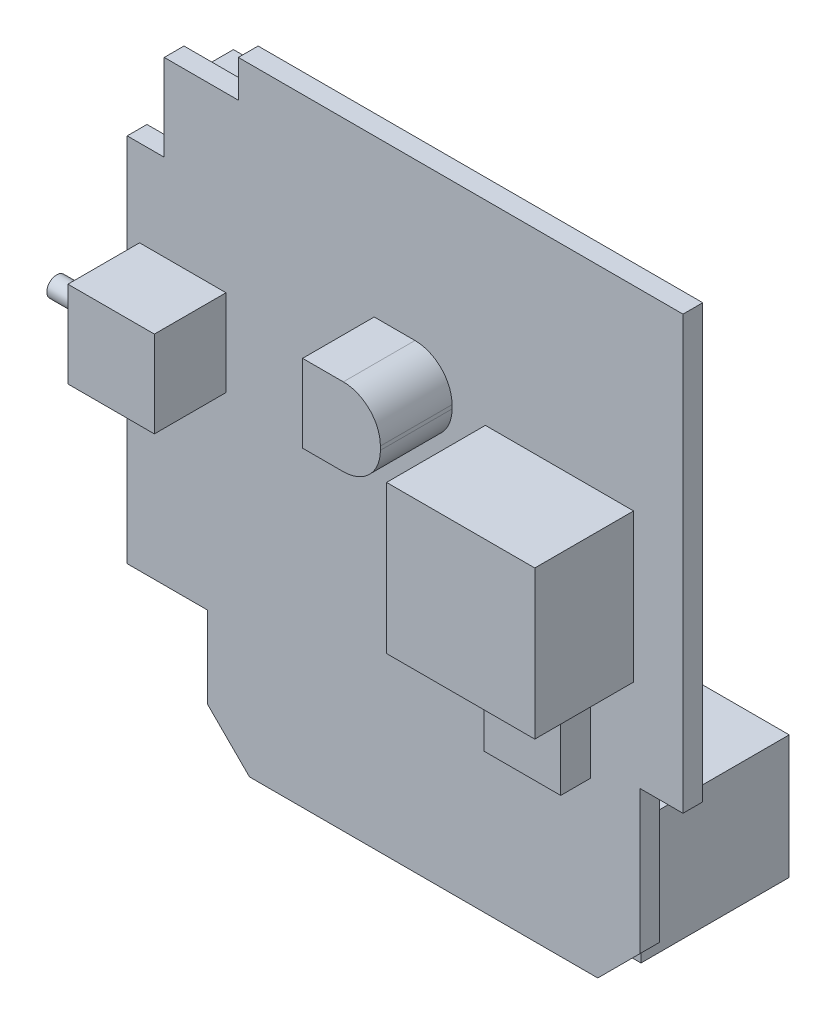
SolidWorks part; units mm, degrees
ref_plane "Front" through (0, 0, 0) normal (0, 0, 1) x (1, 0, 0)
ref_plane "Top" through (0, 0, 0) normal (0, 1, 0) x (1, 0, 0)
ref_plane "Right" through (0, 0, 0) normal (1, 0, 0) x (0, 0, -1)
sketch "Sketch1" plane through (0, 0, 0) normal (0, 0, 1) x (1, 0, 0)
  line L0 (41.5, 3.4) -> (38.1, 0)
  line L1 (9.9, 0) -> (38.1, 0)
  line L2 (6.5, 3.4) -> (6.5, 10)
  line L3 (9, 50) -> (45, 50)
  line L4 (45, 15) -> (45, 50)
  line L5 (45, 15) -> (41.5, 15)
  line L6 (6.5, 3.4) -> (9.9, 0)
  line L7 (41.5, 15) -> (41.5, 3.4)
  line L8 (0, 40) -> (0, 10)
  line L9 (6.5, 10) -> (0, 10)
  line L10 (3, 47) -> (3, 40)
  line L11 (3, 40) -> (0, 40)
  line L12 (9, 50) -> (9, 47)
  line L13 (9, 47) -> (3, 47)
  dimension "D2" = 50
  dimension "D3" = 41.5
  dimension "D4" = 135
  dimension "D5" = 45
  dimension "D6" = 10
  dimension "D7" = 3
  dimension "D8" = 40
  dimension "D9" = 135
  dimension "D10" = 6.5
  dimension "D11" = 47
  dimension "D12" = 9
  dimension "D13" = 3.4
  dimension "D14" = 3.4
  dimension "D15" = 15
extrude "Extrude1" add sketch "Sketch1" along normal blind 1.6
sketch "Sketch3" plane through (0, 0, 0) normal (0, 0, -1) x (-1, 0, 0)
  line L1 (-4.5, 46.25) -> (-10.5, 46.25)
  line L2 (-4.5, 46.25) -> (-4.5, 44.25)
  line L3 (-4.5, 44.25) -> (-10.5, 44.25)
  line L4 (-10.5, 46.25) -> (-10.5, 44.25)
  line L5 (-4.5, 16.75) -> (-10.5, 16.75)
  line L6 (-4.5, 16.75) -> (-4.5, 14.75)
  line L7 (-4.5, 14.75) -> (-10.5, 14.75)
  line L8 (-10.5, 16.75) -> (-10.5, 14.75)
  line L10 (0, 40) -> (0, 10) construction
  line L11 (6, 30.5) -> (-26.2061, 30.5) construction
  line L12 (-45, 50) -> (-9, 50) construction
  dimension "D1" = 2
  dimension "D2" = 6
  dimension "D3" = 13.75
  dimension "D4" = 4.5
  dimension "D5" = 27.5
  dimension "D6" = 19.5
extrude "Extrude3" add sketch "Sketch3" along normal blind 2.5
sketch "Sketch4" plane through (0, 0, 0) normal (0, 0, -1) x (-1, 0, 0)
  line L2 (-45, 15) -> (-45, 50) construction
  line L3 (-40, 1.2) -> (-30, 1.2)
  line L4 (-40, 1.2) -> (-40, 11.2)
  line L5 (-40, 11.2) -> (-30, 11.2)
  line L6 (-30, 1.2) -> (-30, 11.2)
  line L8 (-9.9, 0) -> (-38.1, 0) construction
  line L9 (-29, 1.2) -> (-19, 1.2)
  line L10 (-29, 1.2) -> (-29, 11.2)
  line L11 (-29, 11.2) -> (-19, 11.2)
  line L12 (-19, 1.2) -> (-19, 11.2)
  line L13 (-18, 1.2) -> (-8, 1.2)
  line L14 (-18, 1.2) -> (-18, 11.2)
  line L15 (-18, 11.2) -> (-8, 11.2)
  line L16 (-8, 1.2) -> (-8, 11.2)
  dimension "D1" = 10
  dimension "D2" = 10
  dimension "D3" = 5
  dimension "D4" = 1.2
  dimension "D5" = 1
extrude "Extrude4" add sketch "Sketch4" along normal blind 12
sketch "Sketch6" plane through (0, 0, 1.6) normal (0, 0, 1) x (1, 0, 0)
  line L0 (0, 40) -> (0, 10) construction
  line L1 (1, 33) -> (8, 33)
  line L2 (1, 33) -> (1, 26)
  line L3 (1, 26) -> (8, 26)
  line L4 (8, 33) -> (8, 26)
  line L6 (45, 50) -> (9, 50) construction
  dimension "D1" = 7
  dimension "D2" = 1
  dimension "D3" = 17
  dimension "D4" = 7
extrude "Extrude5" add sketch "Sketch6" along normal blind 5.8
sketch "Sketch8" plane through (1, 0, 4) normal (1, 0, 0) x (0, 0, -1)
  line L0 (-0.5, 33) -> (-0.5, 26) construction
  line L3 (-3.4, 33) -> (2.4, 33) construction
  line L4 (-3.4, 26) -> (2.4, 26) construction
  circle A0 centre (-0.5, 29.5) radius 0.8
  dimension "D1" = 1.6
extrude "Extrude7" add sketch "Sketch8" against normal blind 3.81
sketch "Sketch9" plane through (0, 0, 1.6) normal (0, 0, 1) x (1, 0, 0)
  line L0 (0, 40) -> (0, 10) construction
  line L1 (20, 37.3) -> (26.3, 37.3)
  line L2 (20, 37.3) -> (20, 31)
  line L3 (20, 31) -> (26.3, 31)
  line L4 (26.3, 37.3) -> (26.3, 31)
  line L5 (9.9, 0) -> (38.1, 0) construction
  dimension "D1" = 20
  dimension "D2" = 31
  dimension "D3" = 6.3
  dimension "D4" = 6.3
extrude "Extrude8" add sketch "Sketch9" along normal blind 5.8
fillet "Fillet1" radius 3 2 edges at (26.3, 31, 4.5) (26.3, 37.3, 4.5)
sketch "Sketch10" plane through (0, 0, 1.6) normal (0, 0, 1) x (1, 0, 0)
  line L0 (0, 40) -> (0, 10) construction
  line L1 (29, 22.2) -> (41, 22.2)
  line L2 (29, 22.2) -> (29, 34.2)
  line L3 (29, 34.2) -> (41, 34.2)
  line L4 (41, 22.2) -> (41, 34.2)
  line L5 (9.9, 0) -> (38.1, 0) construction
  dimension "D1" = 29
  dimension "D2" = 22.2
  dimension "D3" = 12
  dimension "D4" = 12
extrude "Extrude9" add sketch "Sketch10" along normal blind 8
sketch "Sketch11" plane through (0, 0, 1.6) normal (0, 0, 1) x (1, 0, 0)
  line L0 (0, 40) -> (0, 10) construction
  line L1 (31.3, 13.7) -> (37.5, 13.7)
  line L2 (31.3, 13.7) -> (31.3, 20.4)
  line L3 (31.3, 20.4) -> (37.5, 20.4)
  line L4 (37.5, 13.7) -> (37.5, 20.4)
  line L5 (9.9, 0) -> (38.1, 0) construction
  dimension "D1" = 31.3
  dimension "D2" = 13.7
  dimension "D3" = 6.2
  dimension "D4" = 6.7
extrude "Extrude10" add sketch "Sketch11" along normal blind 2.4
